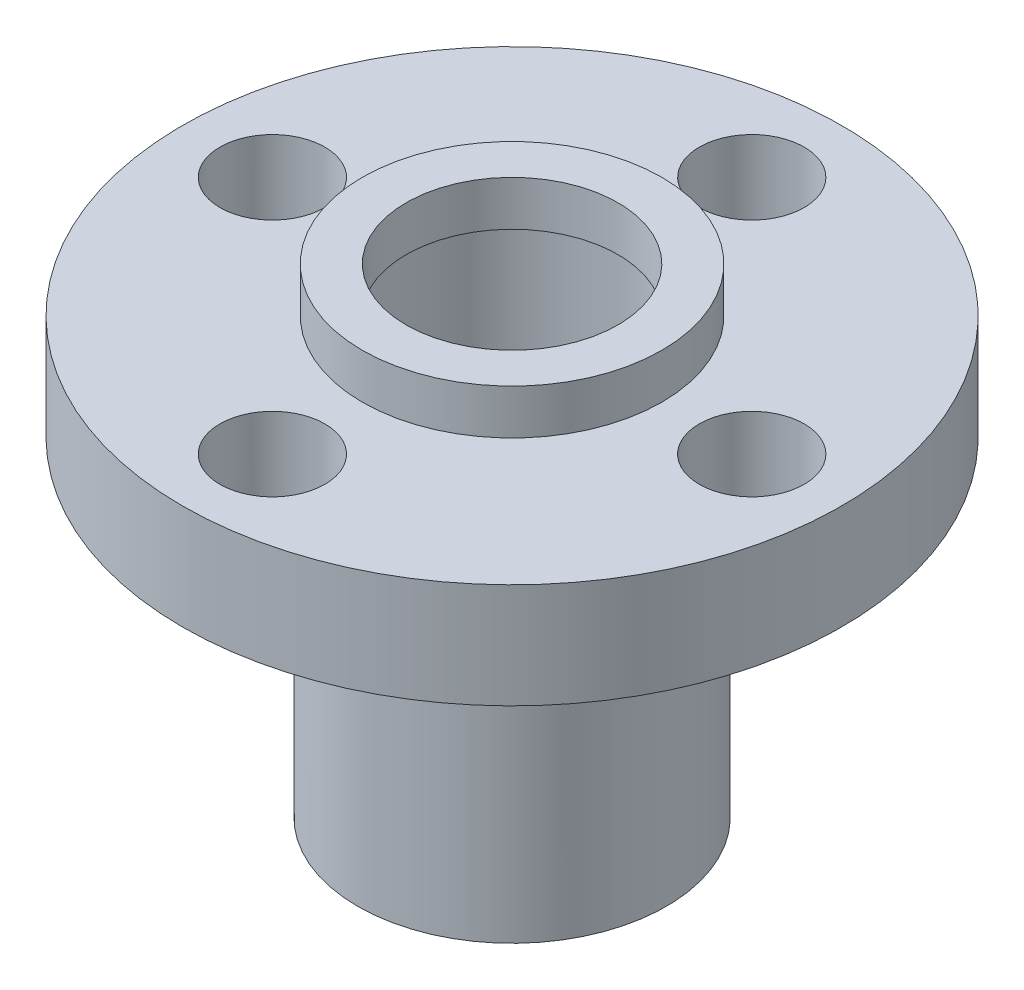
SolidWorks part; units mm, degrees
ref_plane "前视基准面" through (0, 0, 0) normal (0, 0, 1) x (1, 0, 0)
ref_plane "上视基准面" through (0, 0, 0) normal (0, 1, 0) x (1, 0, 0)
ref_plane "右视基准面" through (0, 0, 0) normal (1, 0, 0) x (0, 0, -1)
sketch "草图1" plane through (0, 0, 0) normal (0, 1, 0) x (1, 0, 0)
  circle A0 centre (0, 0) radius 4
  circle A1 centre (0, 0) radius 8 construction
  circle A2 centre (0, 0) radius 11
  circle A3 centre (0, 0) radius 5.15
  dimension "D1" = 10.3
  dimension "D2" = 16
  dimension "D3" = 22
  dimension "D4" = 8
extrude "凸台-拉伸2" add sketch "草图1" along normal blind 3.5 contours A2
sketch "草图2" plane through (0, 0, 0) normal (0, -1, 0) x (1, 0, 0)
  circle A0 centre (0, 0) radius 5.15
  dimension "D1" = 10.3
extrude "凸台-拉伸3" add sketch "草图2" along normal blind 11
sketch "草图3" plane through (0, -11, 0) normal (0, -1, 0) x (1, 0, 0)
  circle A0 centre (0, 0) radius 4
  dimension "D1" = 8
extrude "切除-拉伸1" cut sketch "草图3" against normal through all both and the other way through all
sketch "草图4" plane through (0, 3.5, 0) normal (0, 1, 0) x (1, 0, 0)
  circle A0 centre (0, 0) radius 8 construction
  circle A1 centre (0, 8) radius 1.75
  dimension "D1" = 16
  dimension "D2" = 3.5
extrude "切除-拉伸4" cut sketch "草图4" against normal up to next contours A1
pattern_circular "阵列(圆周)6" count 4 over 360 about axis through (0, 0, 0) along (0, 1, 0) of "切除-拉伸4"
sketch "草图6" plane through (0, 0, 0) normal (0, 1, 0) x (1, 0, 0)
  line L0 (0, -11) -> (0, 11) construction
  circle A0 centre (0, 0) radius 11 construction
sketch "草图7" plane through (0, 3.5, 0) normal (0, 1, 0) x (1, 0, 0)
  line L0 (0, -11) -> (0, 11) construction
  circle A0 centre (0, 0) radius 5
  dimension "D1" = 10
extrude "凸台-拉伸4" add sketch "草图7" along normal blind 1.5
sketch "草图8" plane through (0, 5, 0) normal (0, 1, 0) x (1, 0, 0)
  line L0 (0, -11) -> (0, 11) construction
  circle A0 centre (0, 0) radius 3.5351
extrude "切除-拉伸5" cut sketch "草图8" against normal through all
